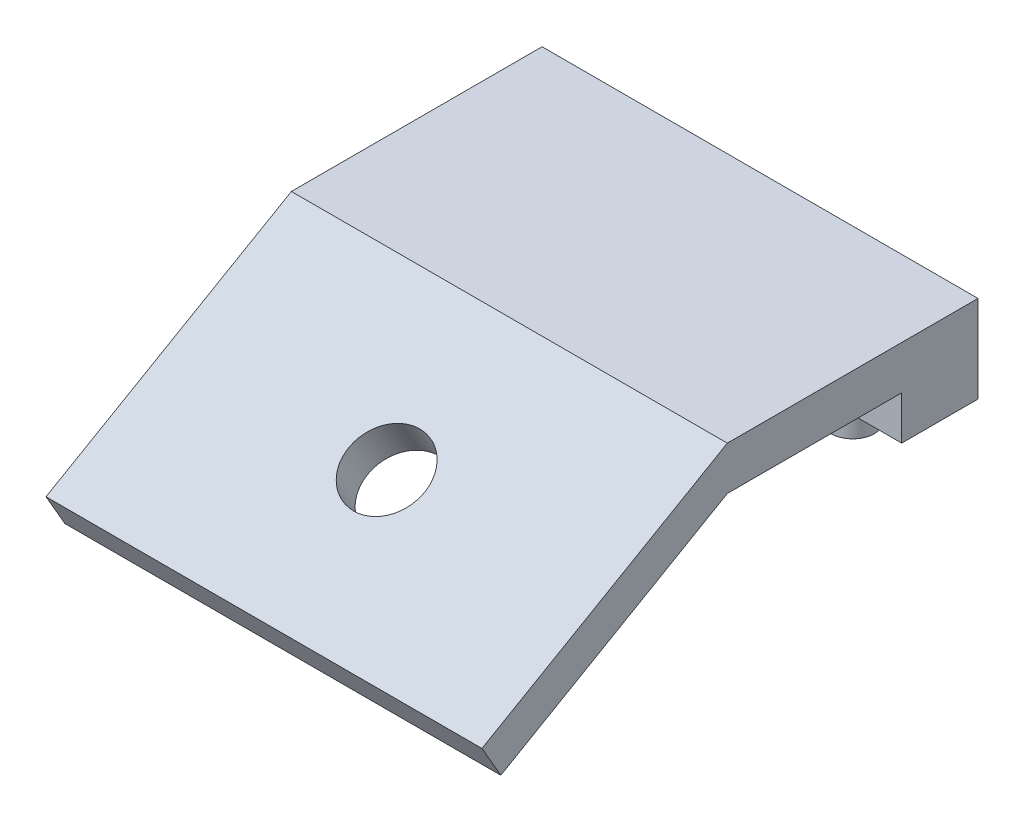
SolidWorks part; units mm, degrees
ref_plane "Front" through (0, 0, 0) normal (0, 0, 1) x (1, 0, 0)
ref_plane "Top" through (0, 0, 0) normal (0, 1, 0) x (1, 0, 0)
ref_plane "Right" through (0, 0, 0) normal (1, 0, 0) x (0, 0, -1)
sketch "Croquis1" plane through (0, 0, 0) normal (0, 1, 0) x (1, 0, 0)
  line L0 (-1000, 0) -> (49000, 0) construction
  line L1 (-10, -1.75) -> (10, -1.75)
  line L2 (-10, -1.75) -> (-10, 1.75)
  line L3 (-10, 1.75) -> (10, 1.75)
  line L4 (10, -1.75) -> (10, 1.75)
  line L5 (-10, -1.75) -> (10, 1.75) construction
  line L6 (-10, 1.75) -> (10, -1.75) construction
  line L7 (0, -1000) -> (0, 49000) construction
  point P0 (0, 0)
  dimension "D1" = 20
  dimension "D2" = 3.5
extrude "Saliente-Extruir1" add sketch "Croquis1" along normal blind 4
sketch "Croquis2" plane through (0, 0, 0) normal (0, -1, 0) x (1, 0, 0)
  line L0 (-1000, 0) -> (49000, 0) construction
  line L1 (0, -1000) -> (0, 49000) construction
  line L2 (3, -1000) -> (3, 49000) construction
  line L3 (-3, -1000) -> (-3, 49000) construction
  circle A0 centre (0, 0) radius 1
  circle A1 centre (-6, 0) radius 1
  circle A2 centre (6, 0) radius 1
  dimension "D1" = 2
  dimension "D2" = 3
  dimension "D3" = 3
extrude "Saliente-Extruir2" add sketch "Croquis2" along normal blind 2
sketch "Croquis3" plane through (0, 0, 1.75) normal (0, 0, 1) x (1, 0, 0)
  line L0 (0, -1000) -> (0, 49000) construction
  line L1 (-1010, 2) -> (48990, 2) construction
  line L2 (-10, 4) -> (-10, 0) construction
  line L3 (10, 4) -> (10, 0) construction
  line L4 (-10, 4) -> (10, 4)
  line L5 (-10, 4) -> (-10, 2)
  line L6 (-10, 2) -> (10, 2)
  line L7 (10, 4) -> (10, 2)
  point P8 (-10, 2)
extrude "Saliente-Extruir3" add sketch "Croquis3" along normal blind 8
ref_plane "Plano1" through (0, -3.7219, 6.4465) normal (0, -0.5, 0.866) x (1, 0, 0)
sketch "Croquis4" plane through (0, -3.7219, 6.4465) normal (0, -0.5, 0.866) x (1, 0, 0)
  line L1 (-10, 6.6071) -> (10, 6.6071)
  line L2 (-10, 6.6071) -> (-10, 8.3391)
  line L3 (-10, 8.3391) -> (10, 8.3391)
  line L4 (10, 6.6071) -> (10, 8.3391)
extrude "Saliente-Extruir4" add sketch "Croquis4" along normal blind 12 and the other way up to next
sketch "Croquis5" plane through (0, 7.2219, 4.1696) normal (0, 0.866, 0.5) x (1, 0, 0)
  line L0 (-10, -19.4437) -> (10, -6.4437) construction
  line L1 (-10, -6.4437) -> (10, -19.4437) construction
  circle A0 centre (0, -12.9437) radius 1.75
  dimension "D1" = 3.5
extrude "Cortar-Extruir1" cut sketch "Croquis5" against normal through all
